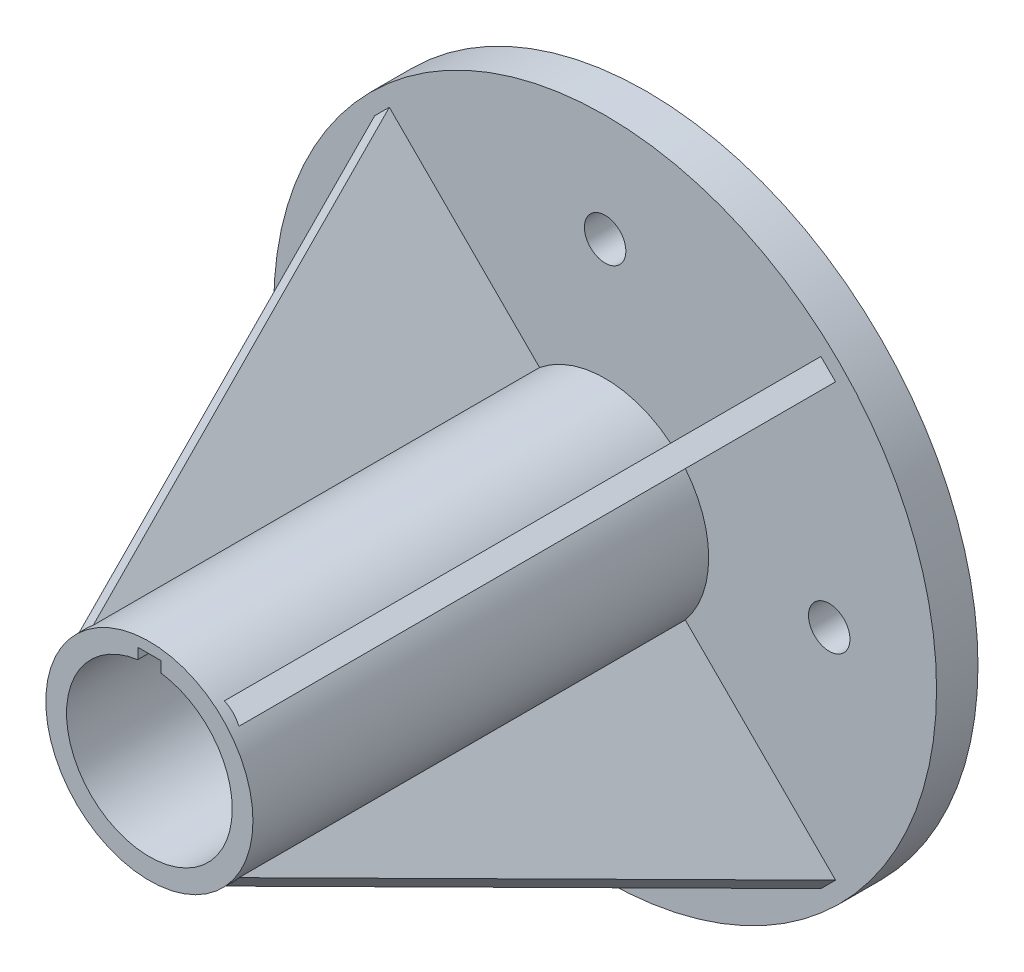
SolidWorks part; units mm, degrees
ref_plane "Front Plane" through (0, 0, 0) normal (0, 0, 1) x (1, 0, 0)
ref_plane "Top Plane" through (0, 0, 0) normal (0, 1, 0) x (1, 0, 0)
ref_plane "Right Plane" through (0, 0, 0) normal (1, 0, 0) x (0, 0, -1)
sketch "Sketch1" plane through (0, 0, 0) normal (0, 0, 1) x (1, 0, 0)
  line L0 (0, 0) -> (0, 12.7) construction
  circle A0 centre (0, 0) radius 12.7
  circle A1 centre (0, 0) radius 15.875
  dimension "D1" = 25.4
  dimension "D2" = 31.75
extrude "Extrude1" add sketch "Sketch1" against normal blind 76.2
sketch "Sketch2" plane through (0, 0, 0) normal (0, 0, 1) x (1, 0, 0)
  line L0 (0, 0) -> (0, 12.7) construction
  line L1 (0, 12.7) -> (0, 14.224) construction
  line L2 (1.778, 12.7) -> (1.778, 14.224)
  line L3 (-1.778, 12.7) -> (-1.778, 14.224)
  line L4 (-1.778, 14.224) -> (1.778, 14.224)
  line L5 (-1.778, 12.7) -> (-1.778, 12.3612)
  line L6 (-1.778, 12.3612) -> (1.778, 12.3612)
  line L7 (1.778, 12.3612) -> (1.778, 12.7)
  circle A1 centre (0, 0) radius 12.7 construction
  dimension "D1" = 1.524
  dimension "D2" = 1.778
  dimension "D3" = 1.778
extrude "Extrude2" cut sketch "Sketch2" against normal blind 25.4
ref_plane "Plane1" through (0, 0, -76.2) normal (0, 0, 1) x (1, 0, 0)
sketch "Sketch3" plane through (0, 0, -76.2) normal (0, 0, 1) x (1, 0, 0)
  circle A0 centre (0, 0) radius 15.875 construction
  circle A1 centre (0, 0) radius 15.875
  circle A2 centre (0, 0) radius 50.8
  dimension "D1" = 101.6
extrude "Extrude3" add sketch "Sketch3" along normal blind 6.35
sketch "Sketch4" plane through (0, 0, -76.2) normal (0, 0, 1) x (1, 0, 0)
  line L0 (0, 0) -> (0, 34.3503) construction
  circle A0 centre (0, 34.3503) radius 3.175
  circle A1 centre (34.3503, 0) radius 3.175
  circle A2 centre (0, -34.3503) radius 3.175
  circle A3 centre (-34.3503, 0) radius 3.175
  dimension "D1" = 6.35
extrude "Extrude5" cut sketch "Sketch4" along normal blind 7.62
sketch "Sketch5" plane through (0, 0, 0) normal (0, 1, 0) x (1, 0, 0)
  line L0 (0, -3.9918) -> (0, 81.1914) construction
ref_plane "Plane2" through (0, 0, 0) normal (0.7071, 0.7071, 0) x (0, 0, -1)
sketch "Sketch6" plane through (0, 0, 0) normal (0.7071, 0.7071, 0) x (0, 0, -1)
  line L0 (1.6036, -15.875) -> (69.85, -48.3597)
  line L1 (69.85, 50.8) -> (69.85, -50.8) construction
  line L2 (0, -15.875) -> (69.85, -15.875) construction
rib "Rib4" sketch "Sketch6" sketch "Sketch6" thickness 3.175 extrusion direction parallel to sketch draft on no parameters "D1"=3.175
pattern_circular "CirPattern1" count 4 over 360 about axis through (0, 0, 0) along (0, 0, 1) of "Rib4"
